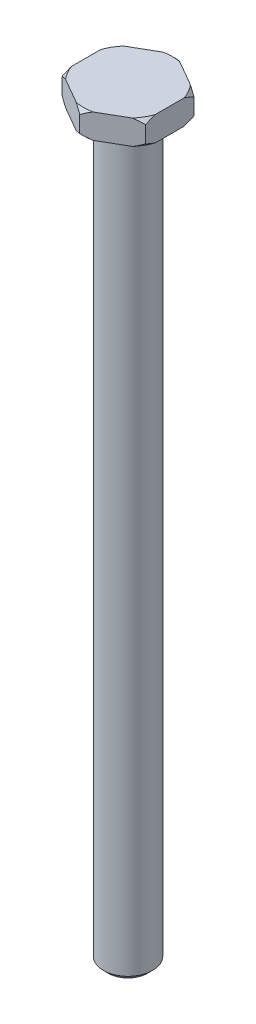
SolidWorks part; units mm, degrees
ref_plane "Front Plane" through (0, 0, 0) normal (0, 0, 1) x (1, 0, 0)
ref_plane "Top Plane" through (0, 0, 0) normal (0, 1, 0) x (1, 0, 0)
ref_plane "Right Plane" through (0, 0, 0) normal (1, 0, 0) x (0, 0, -1)
sketch "Sketch2" plane through (0, 0, 0) normal (1, 0, 0) x (0, 0, -1)
  line L0 (0, 23.6049) -> (0, -15.9787) construction
  line L1 (-10, 76.5) -> (-10, 73.5)
  line L2 (-9, 72.5) -> (-5, 72.5)
  line L3 (-5, 72.5) -> (-5, -76.5)
  line L4 (-4, -77.5) -> (0, -77.5)
  line L5 (-9, 77.5) -> (0, 77.5)
  line L6 (0, -77.5) -> (0, 77.5)
  line L7 (-5, -76.5) -> (-4, -77.5)
  line L8 (-10, 73.5) -> (-9, 72.5)
  line L9 (-10, 76.5) -> (-9, 77.5)
  point P3 (-10, 77.5)
  point P4 (-10, 72.5)
  point P7 (-5, -77.5)
  point P8 (0, 0)
  dimension "D1" = 10
  dimension "D2" = 150
  dimension "D3" = 5
  dimension "D4" = 20
revolve "Revolve1" add sketch "Sketch2" angle 360 about L0
thread "Thread1" pitch 2 start angle 0, offset 5, length 0, pitch 2, diameter 8
ref_plane "Plane2" through (4, -16.5, 0) normal (0, 0, 1) x (1, 0, 0)
sketch "Thread Profile2" plane through (4, -16.5, 0) normal (0, 0, 1) x (1, 0, 0)
  line L0 (0, 0) -> (0, 2) construction
  line L1 (0, 0) -> (1.0825, 0.625)
  line L2 (1.0825, 0.625) -> (1.0825, 0.875)
  line L3 (1.0825, 0.875) -> (0, 1.5)
  line L4 (1.0825, 0.75) -> (0, 0.75) construction
  line L11 (0, 0) -> (0, 1.5)
  point P2 (0, 0)
  dimension "Pitch" = 2
  dimension "Profile_Angle" = 60
  dimension "Profile_Land" = 0.25
  dimension "Profile_Height" = 1.0825
sketch "Sketch3" plane through (0, 77.5, 0) normal (0, 1, 0) x (1, 0, 0)
  line L1 (0, -9.815) -> (8.5, -4.9075)
  line L2 (8.5, -4.9075) -> (8.5, 4.9075)
  line L3 (8.5, 4.9075) -> (0, 9.815)
  line L4 (0, 9.815) -> (-8.5, 4.9075)
  line L5 (-8.5, 4.9075) -> (-8.5, -4.9075)
  line L6 (-8.5, -4.9075) -> (0, -9.815)
  circle A0 centre (0, 0) radius 8.5 construction
  circle A1 centre (0, 0) radius 15.4433
  dimension "D1" = 17
extrude "Cut-Extrude1" cut sketch "Sketch3" against normal up to surface (5 mm away) up to face at (0, 72.5, 5)
